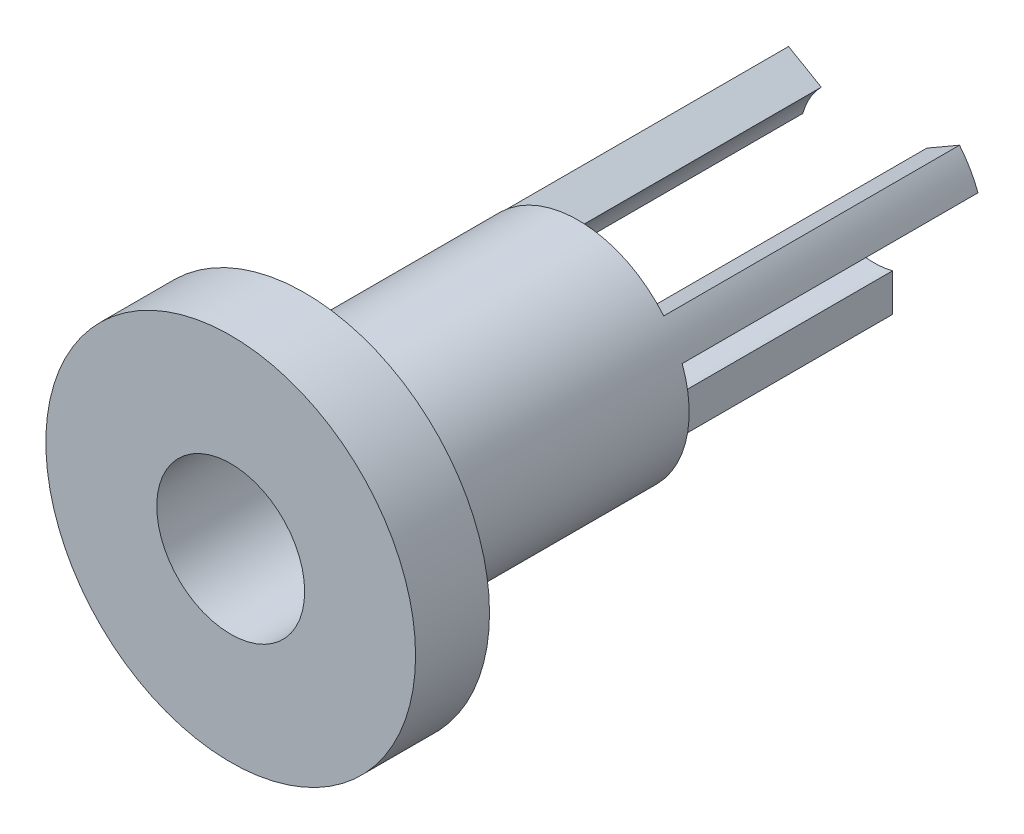
SolidWorks part; units mm, degrees
material "ABS PC"
ref_plane "Front Plane" through (0, 0, 0) normal (0, 0, 1) x (1, 0, 0)
ref_plane "Top Plane" through (0, 0, 0) normal (0, 1, 0) x (1, 0, 0)
ref_plane "Right Plane" through (0, 0, 0) normal (1, 0, 0) x (0, 0, -1)
sketch "Sketch1" plane through (0, 0, 0) normal (0, 0, 1) x (1, 0, 0)
  circle A0 centre (0, 0) radius 0.5
  circle A1 centre (0, 0) radius 0.75
  dimension "D1" = 1
  dimension "D2" = 1.5
extrude "Boss-Extrude1" add sketch "Sketch1" along normal blind 1.85
sketch "Sketch2" plane through (0, 0, 1.85) normal (0, 0, 1) x (1, 0, 0)
  circle A0 centre (0, 0) radius 0.5 construction
  circle A1 centre (0, 0) radius 0.5
  circle A2 centre (0, 0) radius 1.25
  dimension "D1" = 2.5
sketch "Sketch4" plane through (0, 0, 0) normal (0, 0, -1) x (-1, 0, 0)
  line L0 (0, 0) -> (0, -0.75) construction
  line L1 (0, 0) -> (0.6495, 0.375) construction
  line L2 (0.712, 0.2667) -> (0.587, 0.4833)
  line L3 (-0.125, -0.4841) -> (-0.125, -0.75)
  line L4 (0.125, -0.4841) -> (0.125, -0.75)
  line L5 (0.587, 0.4833) -> (0.3568, 0.3503)
  line L6 (0, 0) -> (-0.6495, 0.375) construction
  line L7 (0.125, -0.75) -> (-0.125, -0.75)
  line L8 (0.712, 0.2667) -> (0.4818, 0.1338)
  line L9 (-0.587, 0.4833) -> (-0.712, 0.2667)
  line L10 (-0.587, 0.4833) -> (-0.3568, 0.3503)
  line L11 (-0.712, 0.2667) -> (-0.4818, 0.1338)
  circle A0 centre (0, 0) radius 0.75 construction
  circle A1 centre (0, 0) radius 0.5
  circle A3 centre (0, 0) radius 0.5 construction
  circle A4 centre (0, 0) radius 0.75 construction
  point P11 (0.6495, 0.375)
  point P18 (0, -0.75)
  point P21 (-0.6495, 0.375)
  circle M2 centre (0, 0) radius 0.75
  circle M3 centre (0, 0) radius 0.5
  dimension "D1" = 0.25
  dimension "D2" = 120
  dimension "D3" = 120
extrude "Boss-Extrude2" add sketch "Sketch2" along normal blind 0.5
extrude "Boss-Extrude3" add sketch "Sketch4" along normal blind 2 contours L11 L10 M2 M3 | L8 L5 M2 M3 | L4 L3 M3 M2
